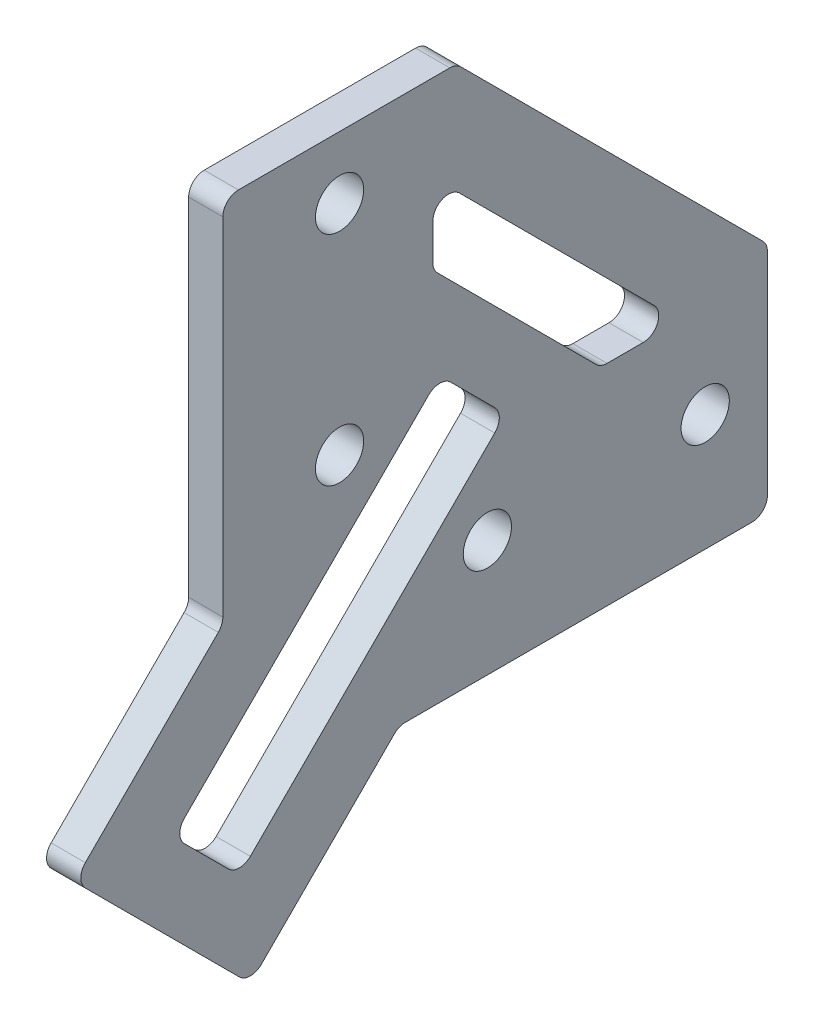
SolidWorks part; units mm, degrees
material "Thornel Mat VMA"
ref_plane "前视基准面" through (0, 0, 0) normal (0, 0, 1) x (1, 0, 0)
ref_plane "上视基准面" through (0, 0, 0) normal (0, 1, 0) x (1, 0, 0)
ref_plane "右视基准面" through (0, 0, 0) normal (1, 0, 0) x (0, 0, -1)
sketch "草图1" plane through (0, 0, 0) normal (1, 0, 0) x (0, 0, -1)
  line L1 (11.3137, 0) -> (35, 0)
  line L2 (0, 35) -> (15, 35)
  line L3 (15, 35) -> (35, 15)
  line L4 (35, 15) -> (35, 0)
  line L5 (0, 0) -> (15, 15) construction
  line L6 (13.9393, 18.182) -> (18.182, 13.9393)
  line L7 (13.9393, 18.182) -> (-3.182, 1.0607)
  line L8 (18.182, 13.9393) -> (1.0607, -3.182)
  line L9 (-3.182, 1.0607) -> (1.0607, -3.182)
  line L10 (13.9393, 18.182) -> (1.0607, -3.182) construction
  line L11 (18.182, 13.9393) -> (-3.182, 1.0607) construction
  line L12 (0, 11.3137) -> (-9.5459, 1.7678)
  line L13 (-9.5459, 1.7678) -> (1.7678, -9.5459)
  line L14 (1.7678, -9.5459) -> (11.3137, 0)
  line L15 (0, 11.3137) -> (0, 35)
  line L16 (7.5, 35) -> (7.5, 22.7811) construction
  line L17 (13.5, 29.4289) -> (13.5, 24.2782)
  line L18 (13.5, 24.2782) -> (24.2782, 13.5)
  line L19 (24.2782, 13.5) -> (29.4289, 13.5)
  line L20 (29.4289, 13.5) -> (13.5, 29.4289)
  circle A0 centre (7.5, 31) radius 1.55
  circle A1 centre (7.5, 17) radius 1.55
  circle A2 centre (31, 7.5) radius 1.55
  circle A3 centre (17, 7.5) radius 1.55
  point P8 (7.5, 7.5)
  point P16 (6.5407, -4.773)
  dimension "D10" = 3.1
  dimension "D1" = 15
  dimension "D2" = 35
  dimension "D3" = 1.5
  dimension "D4" = 6
  dimension "D5" = 5
  dimension "D6" = 6
  dimension "D7" = 4
  dimension "D8" = 14
  dimension "D9" = 4
  dimension "D11" = 5
  dimension "D12" = 4
extrude "凸台-拉伸1" add sketch "草图1" along normal blind 2.2
fillet "圆角1" radius 1 16 edges at (1.1, 13.5, -29.4289) (1.1, 29.4289, -13.5) (1.1, 24.2782, -13.5) (1.1, 13.5, -24.2782) (1.1, 35, -15) (1.1, 15, -35) (1.1, 0, -35) (1.1, 0, -11.3137) (1.1, -9.5459, -1.7678) (1.1, 1.7678, 9.5459) (1.1, 11.3137, 0) (1.1, 1.0607, 3.182) (1.1, -3.182, -1.0607) (1.1, 13.9393, -18.182) (1.1, 18.182, -13.9393) (1.1, 35, 0)
